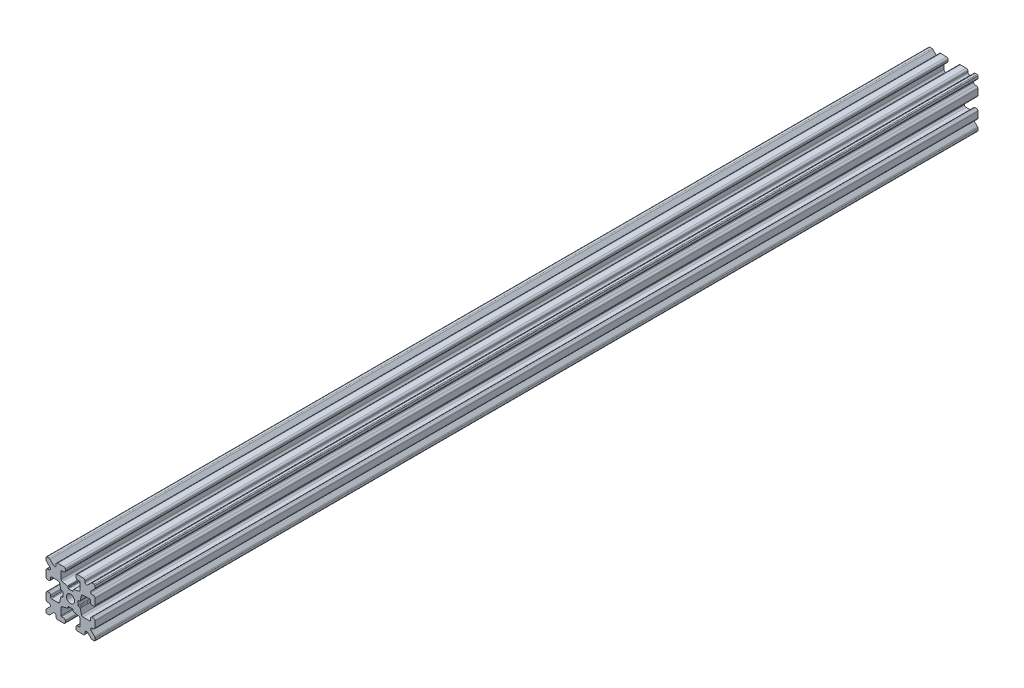
SolidWorks part; units mm, degrees
ref_plane "Front Plane" through (0, 0, 0) normal (0, 0, 1) x (1, 0, 0)
ref_plane "Top Plane" through (0, 0, 0) normal (0, 1, 0) x (1, 0, 0)
ref_plane "Right Plane" through (0, 0, 0) normal (1, 0, 0) x (0, 0, -1)
ref_plane "Plane1" through (0, 0, -105) normal (0, 0, -1) x (-1, 0, 0)
sketch "Sketch1" plane through (0, 0, -105) normal (0, 0, -1) x (-1, 0, 0)
  line L0 (0.8255, 2.7749) -> (0.8255, 2.5471)
  line L1 (0.6255, 2.3471) -> (-0.6255, 2.3471)
  line L2 (-0.8255, 2.5471) -> (-0.8255, 2.7749)
  line L3 (-0.9818, 2.97) -> (-2.5094, 3.3124)
  line L4 (-2.9, 3.8003) -> (-2.9, 5.9)
  line L5 (-2.7, 6.1) -> (-2.1, 6.1)
  line L6 (-1.6, 6.6) -> (-1.6, 7)
  line L7 (-2.1, 7.5) -> (-3.9, 7.5)
  line L8 (-4.4, 7) -> (-4.4, 6.6678)
  line L9 (-5.2536, 6.3142) -> (-6.2929, 7.3536)
  line L10 (-6.6464, 7.5) -> (-7.25, 7.5)
  line L11 (-7.5, 7.25) -> (-7.5, 6.6464)
  line L12 (-7.3536, 6.2929) -> (-6.3142, 5.2536)
  line L13 (-6.6678, 4.4) -> (-7, 4.4)
  line L14 (-7.5, 3.9) -> (-7.5, 2.1)
  line L15 (-7, 1.6) -> (-6.6, 1.6)
  line L16 (-6.1, 2.1) -> (-6.1, 2.7)
  line L17 (-5.9, 2.9) -> (-3.8003, 2.9)
  line L18 (-3.3124, 2.5094) -> (-2.97, 0.9818)
  line L19 (-2.7749, 0.8255) -> (-2.5471, 0.8255)
  line L20 (-2.3471, 0.6255) -> (-2.3471, -0.6255)
  line L21 (-2.5471, -0.8255) -> (-2.7749, -0.8255)
  line L22 (-2.97, -0.9818) -> (-3.3124, -2.5094)
  line L23 (-3.8003, -2.9) -> (-5.9, -2.9)
  line L24 (-6.1, -2.7) -> (-6.1, -2.1)
  line L25 (-6.6, -1.6) -> (-7, -1.6)
  line L26 (-7.5, -2.1) -> (-7.5, -3.9)
  line L27 (-7, -4.4) -> (-6.6678, -4.4)
  line L28 (-6.3142, -5.2536) -> (-7.3536, -6.2929)
  line L29 (-7.5, -6.6464) -> (-7.5, -7.25)
  line L30 (-7.25, -7.5) -> (-6.6464, -7.5)
  line L31 (-6.2929, -7.3536) -> (-5.2536, -6.3142)
  line L32 (-4.4, -6.6678) -> (-4.4, -7)
  line L33 (-3.9, -7.5) -> (-2.1, -7.5)
  line L34 (-1.6, -7) -> (-1.6, -6.6)
  line L35 (-2.1, -6.1) -> (-2.7, -6.1)
  line L36 (-2.9, -5.9) -> (-2.9, -3.8003)
  line L37 (-2.5094, -3.3124) -> (-0.9818, -2.97)
  line L38 (-0.8255, -2.7749) -> (-0.8255, -2.5471)
  line L39 (-0.6255, -2.3471) -> (0.6255, -2.3471)
  line L40 (0.8255, -2.5471) -> (0.8255, -2.7749)
  line L41 (0.9818, -2.97) -> (2.5094, -3.3124)
  line L42 (2.9, -3.8003) -> (2.9, -5.9)
  line L43 (2.7, -6.1) -> (2.1, -6.1)
  line L44 (1.6, -6.6) -> (1.6, -7)
  line L45 (2.1, -7.5) -> (3.9, -7.5)
  line L46 (4.4, -7) -> (4.4, -6.6678)
  line L47 (5.2536, -6.3142) -> (6.2929, -7.3536)
  line L48 (6.6464, -7.5) -> (7.25, -7.5)
  line L49 (7.5, -7.25) -> (7.5, -6.6464)
  line L50 (7.3536, -6.2929) -> (6.3142, -5.2536)
  line L51 (6.6678, -4.4) -> (7, -4.4)
  line L52 (7.5, -3.9) -> (7.5, -2.1)
  line L53 (7, -1.6) -> (6.6, -1.6)
  line L54 (6.1, -2.1) -> (6.1, -2.7)
  line L55 (5.9, -2.9) -> (3.8003, -2.9)
  line L56 (3.3124, -2.5094) -> (2.97, -0.9818)
  line L57 (2.7749, -0.8255) -> (2.5471, -0.8255)
  line L58 (2.3471, -0.6255) -> (2.3471, 0.6255)
  line L59 (2.5471, 0.8255) -> (2.7749, 0.8255)
  line L60 (2.97, 0.9818) -> (3.3124, 2.5094)
  line L61 (3.8003, 2.9) -> (5.9, 2.9)
  line L62 (6.1, 2.7) -> (6.1, 2.1)
  line L63 (6.6, 1.6) -> (7, 1.6)
  line L64 (7.5, 2.1) -> (7.5, 3.9)
  line L65 (7, 4.4) -> (6.6678, 4.4)
  line L66 (6.3142, 5.2536) -> (7.3536, 6.2929)
  line L67 (7.5, 6.6464) -> (7.5, 7.25)
  line L68 (7.25, 7.5) -> (6.6464, 7.5)
  line L69 (6.2929, 7.3536) -> (5.2536, 6.3142)
  line L70 (4.4, 6.6678) -> (4.4, 7)
  line L71 (3.9, 7.5) -> (2.1, 7.5)
  line L72 (1.6, 7) -> (1.6, 6.6)
  line L73 (2.1, 6.1) -> (2.7, 6.1)
  line L74 (2.9, 5.9) -> (2.9, 3.8003)
  line L75 (2.5094, 3.3124) -> (0.9818, 2.97)
  circle A0 centre (0, 0) radius 1.25
  arc A1 (0.8255, 2.5471) -> (0.6255, 2.3471) centre (0.6255, 2.5471) cw
  arc A2 (-0.6255, 2.3471) -> (-0.8255, 2.5471) centre (-0.6255, 2.5471) cw
  arc A3 (-0.8255, 2.7749) -> (-0.9818, 2.97) centre (-1.0255, 2.7749) ccw
  arc A4 (-2.5094, 3.3124) -> (-2.9, 3.8003) centre (-2.4, 3.8003) cw
  arc A5 (-2.9, 5.9) -> (-2.7, 6.1) centre (-2.7, 5.9) cw
  arc A6 (-2.1, 6.1) -> (-1.6, 6.6) centre (-2.1, 6.6) ccw
  arc A7 (-1.6, 7) -> (-2.1, 7.5) centre (-2.1, 7) ccw
  arc A8 (-3.9, 7.5) -> (-4.4, 7) centre (-3.9, 7) ccw
  arc A9 (-4.4, 6.6678) -> (-5.2536, 6.3142) centre (-4.9, 6.6678) cw
  arc A10 (-6.2929, 7.3536) -> (-6.6464, 7.5) centre (-6.6464, 7) ccw
  arc A11 (-7.25, 7.5) -> (-7.5, 7.25) centre (-7.25, 7.25) ccw
  arc A12 (-7.5, 6.6464) -> (-7.3536, 6.2929) centre (-7, 6.6464) ccw
  arc A13 (-6.3142, 5.2536) -> (-6.6678, 4.4) centre (-6.6678, 4.9) cw
  arc A14 (-7, 4.4) -> (-7.5, 3.9) centre (-7, 3.9) ccw
  arc A15 (-7.5, 2.1) -> (-7, 1.6) centre (-7, 2.1) ccw
  arc A16 (-6.6, 1.6) -> (-6.1, 2.1) centre (-6.6, 2.1) ccw
  arc A17 (-6.1, 2.7) -> (-5.9, 2.9) centre (-5.9, 2.7) cw
  arc A18 (-3.8003, 2.9) -> (-3.3124, 2.5094) centre (-3.8003, 2.4) cw
  arc A19 (-2.97, 0.9818) -> (-2.7749, 0.8255) centre (-2.7749, 1.0255) ccw
  arc A20 (-2.5471, 0.8255) -> (-2.3471, 0.6255) centre (-2.5471, 0.6255) cw
  arc A21 (-2.3471, -0.6255) -> (-2.5471, -0.8255) centre (-2.5471, -0.6255) cw
  arc A22 (-2.7749, -0.8255) -> (-2.97, -0.9818) centre (-2.7749, -1.0255) ccw
  arc A23 (-3.3124, -2.5094) -> (-3.8003, -2.9) centre (-3.8003, -2.4) cw
  arc A24 (-5.9, -2.9) -> (-6.1, -2.7) centre (-5.9, -2.7) cw
  arc A25 (-6.1, -2.1) -> (-6.6, -1.6) centre (-6.6, -2.1) ccw
  arc A26 (-7, -1.6) -> (-7.5, -2.1) centre (-7, -2.1) ccw
  arc A27 (-7.5, -3.9) -> (-7, -4.4) centre (-7, -3.9) ccw
  arc A28 (-6.6678, -4.4) -> (-6.3142, -5.2536) centre (-6.6678, -4.9) cw
  arc A29 (-7.3536, -6.2929) -> (-7.5, -6.6464) centre (-7, -6.6464) ccw
  arc A30 (-7.5, -7.25) -> (-7.25, -7.5) centre (-7.25, -7.25) ccw
  arc A31 (-6.6464, -7.5) -> (-6.2929, -7.3536) centre (-6.6464, -7) ccw
  arc A32 (-5.2536, -6.3142) -> (-4.4, -6.6678) centre (-4.9, -6.6678) cw
  arc A33 (-4.4, -7) -> (-3.9, -7.5) centre (-3.9, -7) ccw
  arc A34 (-2.1, -7.5) -> (-1.6, -7) centre (-2.1, -7) ccw
  arc A35 (-1.6, -6.6) -> (-2.1, -6.1) centre (-2.1, -6.6) ccw
  arc A36 (-2.7, -6.1) -> (-2.9, -5.9) centre (-2.7, -5.9) cw
  arc A37 (-2.9, -3.8003) -> (-2.5094, -3.3124) centre (-2.4, -3.8003) cw
  arc A38 (-0.9818, -2.97) -> (-0.8255, -2.7749) centre (-1.0255, -2.7749) ccw
  arc A39 (-0.8255, -2.5471) -> (-0.6255, -2.3471) centre (-0.6255, -2.5471) cw
  arc A40 (0.6255, -2.3471) -> (0.8255, -2.5471) centre (0.6255, -2.5471) cw
  arc A41 (0.8255, -2.7749) -> (0.9818, -2.97) centre (1.0255, -2.7749) ccw
  arc A42 (2.5094, -3.3124) -> (2.9, -3.8003) centre (2.4, -3.8003) cw
  arc A43 (2.9, -5.9) -> (2.7, -6.1) centre (2.7, -5.9) cw
  arc A44 (2.1, -6.1) -> (1.6, -6.6) centre (2.1, -6.6) ccw
  arc A45 (1.6, -7) -> (2.1, -7.5) centre (2.1, -7) ccw
  arc A46 (3.9, -7.5) -> (4.4, -7) centre (3.9, -7) ccw
  arc A47 (4.4, -6.6678) -> (5.2536, -6.3142) centre (4.9, -6.6678) cw
  arc A48 (6.2929, -7.3536) -> (6.6464, -7.5) centre (6.6464, -7) ccw
  arc A49 (7.25, -7.5) -> (7.5, -7.25) centre (7.25, -7.25) ccw
  arc A50 (7.5, -6.6464) -> (7.3536, -6.2929) centre (7, -6.6464) ccw
  arc A51 (6.3142, -5.2536) -> (6.6678, -4.4) centre (6.6678, -4.9) cw
  arc A52 (7, -4.4) -> (7.5, -3.9) centre (7, -3.9) ccw
  arc A53 (7.5, -2.1) -> (7, -1.6) centre (7, -2.1) ccw
  arc A54 (6.6, -1.6) -> (6.1, -2.1) centre (6.6, -2.1) ccw
  arc A55 (6.1, -2.7) -> (5.9, -2.9) centre (5.9, -2.7) cw
  arc A56 (3.8003, -2.9) -> (3.3124, -2.5094) centre (3.8003, -2.4) cw
  arc A57 (2.97, -0.9818) -> (2.7749, -0.8255) centre (2.7749, -1.0255) ccw
  arc A58 (2.5471, -0.8255) -> (2.3471, -0.6255) centre (2.5471, -0.6255) cw
  arc A59 (2.3471, 0.6255) -> (2.5471, 0.8255) centre (2.5471, 0.6255) cw
  arc A60 (2.7749, 0.8255) -> (2.97, 0.9818) centre (2.7749, 1.0255) ccw
  arc A61 (3.3124, 2.5094) -> (3.8003, 2.9) centre (3.8003, 2.4) cw
  arc A62 (5.9, 2.9) -> (6.1, 2.7) centre (5.9, 2.7) cw
  arc A63 (6.1, 2.1) -> (6.6, 1.6) centre (6.6, 2.1) ccw
  arc A64 (7, 1.6) -> (7.5, 2.1) centre (7, 2.1) ccw
  arc A65 (7.5, 3.9) -> (7, 4.4) centre (7, 3.9) ccw
  arc A66 (6.6678, 4.4) -> (6.3142, 5.2536) centre (6.6678, 4.9) cw
  arc A67 (7.3536, 6.2929) -> (7.5, 6.6464) centre (7, 6.6464) ccw
  arc A68 (7.5, 7.25) -> (7.25, 7.5) centre (7.25, 7.25) ccw
  arc A69 (6.6464, 7.5) -> (6.2929, 7.3536) centre (6.6464, 7) ccw
  arc A70 (5.2536, 6.3142) -> (4.4, 6.6678) centre (4.9, 6.6678) cw
  arc A71 (4.4, 7) -> (3.9, 7.5) centre (3.9, 7) ccw
  arc A72 (2.1, 7.5) -> (1.6, 7) centre (2.1, 7) ccw
  arc A73 (1.6, 6.6) -> (2.1, 6.1) centre (2.1, 6.6) ccw
  arc A74 (2.7, 6.1) -> (2.9, 5.9) centre (2.7, 5.9) cw
  arc A75 (2.9, 3.8003) -> (2.5094, 3.3124) centre (2.4, 3.8003) cw
  arc A76 (0.9818, 2.97) -> (0.8255, 2.7749) centre (1.0255, 2.7749) ccw
extrude "Boss-Extrude1" add sketch "Sketch1" against normal blind 270
